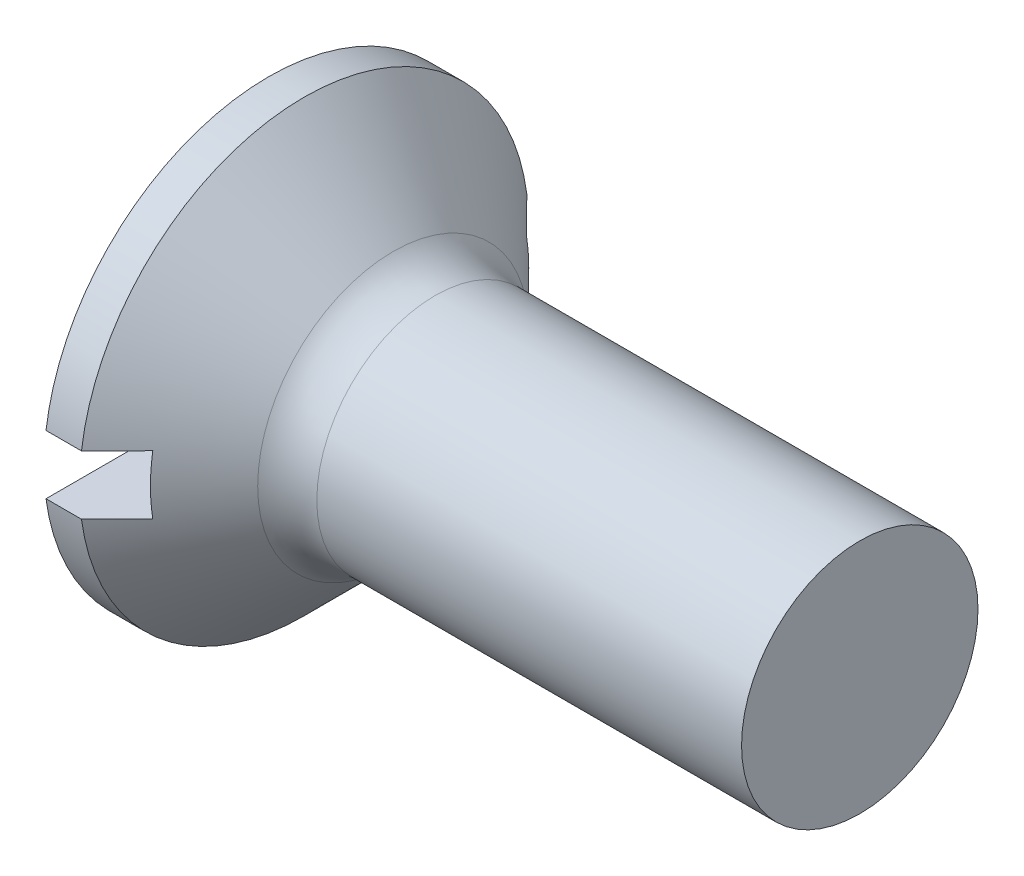
SolidWorks part; units mm, degrees
revolve "Base-Revolve" add sketch "BodySke" angle 360 about L5
sketch "BodySke" plane through (0, 0, 0) normal (0, 0, 1) x (1, 0, 0)
  line L0 (0, 0) -> (0, 1.9)
  line L1 (0, 1.9) -> (0.3, 1.9)
  line L2 (1.2, 1) -> (5, 1)
  line L3 (5, 1) -> (5, 0)
  line L4 (5, 0) -> (0, 0)
  line L5 (-6.35, 0) -> (82.55, 0) construction
  line L6 (1.2, -1) -> (5, -1) construction
  line L7 (0.3, -1.9) -> (1.2, -1) construction
  line L8 (0.3, 1.9) -> (1.2, 1)
  line L9 (0, -1.9) -> (0.3, -1.9) construction
  line L10 (1.6, 2.5875) -> (1.6, -6.9375) construction
  line L11 (0, 6.35) -> (0, -3.175) construction
  dimension "Diameter" = 2
  dimension "Length" = 5
  dimension "Head_ht" = 1.2
  dimension "Head_dia" = 3.8
  dimension "Head_ang" = 90
  dimension "D6" = 0.3
  dimension "Advance" = 0.4
  dimension "Thread_nom" = 5
cosmetic thread "ThreadCosmetic" [suppressed] parameters "Thread_length"=3.4, "Thread_minor"=1.548
extrude "Slot" cut sketch "Sketch2" against normal blind 0.6
sketch "Sketch2" plane through (0, 0, 0) normal (-1, 0, 0) x (0, 0, 1)
  line L0 (-1.9, -0.25) -> (1.9, -0.25)
  line L1 (-1.9, -0.25) -> (-1.9, 0.25)
  line L2 (1.9, 0.25) -> (-1.9, 0.25)
  line L3 (1.9, 0.25) -> (1.9, -0.25)
  dimension "Slot_width" = 0.5
  dimension "D1" = 0.25
  dimension "D2" = 3.8
  dimension "D3" = 1.9
ref_plane "Plane1" through (0, 0, 0) normal (0, 0, 1) x (1, 0, 0)
ref_plane "Plane2" through (0, 0, 0) normal (0, 1, 0) x (1, 0, 0)
ref_plane "Plane3" through (0, 0, 0) normal (1, 0, 0) x (0, 0, -1)
fillet "Fillet1" radius 0.5 1 edges at (1.2, 0, 1)
sketch "ThdSchSke" plane through (0, 0, 0) normal (0, 0, 1) x (1, 0, 0)
  line L0 (1.6, -0.774) -> (1.4418, -1)
  line L1 (1.6, -0.774) -> (1.7582, -1)
  line L2 (1.7582, -1) -> (1.7582, -1.25)
  line L3 (-3.175, 0) -> (5.1513, 0) construction
  line L5 (1.7582, -1.25) -> (1.4418, -1.25)
  line L6 (1.4418, -1.25) -> (1.4418, -1)
  line L7 (0, 1.9) -> (0, 0.25) construction
  dimension "Diameter" = 2
  dimension "Thread_minor" = 1.548
  dimension "Start" = 1.6
revolve "ThreadSchematic" [suppressed] cut sketch "ThdSchSke" angle 360 about L3
pattern_linear "ThdSchPat" [suppressed]
equation "\"D1@Sketch2\" = \"Slot_width@Sketch2\" / 2"
equation "\"D2@Sketch2\" = \"Head_dia@BodySke\""
equation "\"D3@Sketch2\" = \"D2@Sketch2\" / 2"
equation "\"Thread_length@ThreadCosmetic\" = ((sgn( (\"Length@BodySke\" - \"Advance@BodySke\" * 1.0 - \"Head_ht@BodySke\" ) - \"Thread_nom@BodySke\" )-1)*( (\"Length@BodySke\" - \"Advance@BodySke\" * 1.0 - \"Head_ht@BodySke\" ) - \"Thread_nom@BodySke\" ))/-2+ \"Thread_nom@BodySke\""
equation "\"Thread_minor@ThdSchSke\" = \"Thread_minor@ThreadCosmetic\""
equation "\"Diameter@ThdSchSke\" = \"Diameter@BodySke\""
equation "\"Overcut@ThdSchSke\" = \"Diameter@BodySke\" * 1.25"
equation "\"Start@ThdSchSke\" = 0.000001 + \"Length@BodySke\" - \"Thread_length@ThreadCosmetic\"  '---Countersunk---"
equation "\"Num_threads@ThdSchPat\" = int( \"Thread_length@ThreadCosmetic\" / \"Advance@BodySke\" + 0.999 )  + 1"
equation "\"Advance@ThdSchPat\" = \"Thread_length@ThreadCosmetic\" /  (\"Num_threads@ThdSchPat\" - 1) 'relax it"
